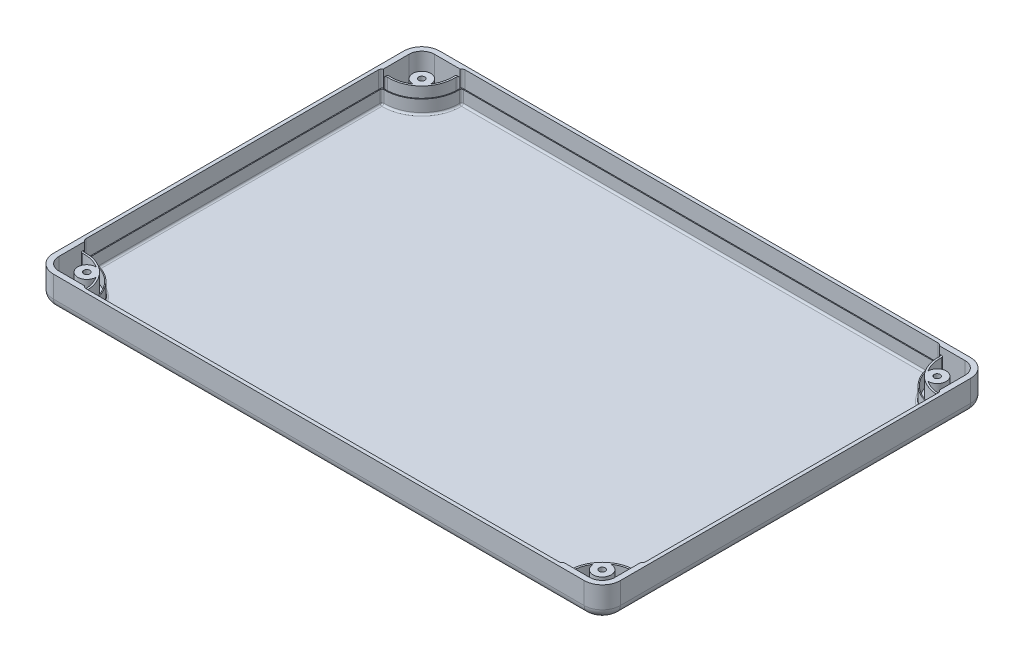
SolidWorks part; units mm, degrees
ref_plane "Alzado" through (0, 0, 0) normal (0, 0, 1) x (1, 0, 0)
ref_plane "Planta" through (0, 0, 0) normal (0, 1, 0) x (1, 0, 0)
ref_plane "Vista lateral" through (0, 0, 0) normal (1, 0, 0) x (0, 0, -1)
sketch "Croquis1" plane through (0, 0, 0) normal (0, 1, 0) x (1, 0, 0)
  line L1 (-147, 107) -> (147, 107)
  line L2 (-157, 97) -> (-157, -97)
  line L3 (-147, -107) -> (147, -107)
  line L4 (157, 97) -> (157, -97)
  line L5 (-157, 107) -> (157, -107) construction
  line L6 (-157, -107) -> (157, 107) construction
  arc A0 (-157, 97) -> (-147, 107) centre (-147, 97) cw
  arc A1 (-147, -107) -> (-157, -97) centre (-147, -97) cw
  arc A2 (157, -97) -> (147, -107) centre (147, -97) cw
  arc A3 (157, 97) -> (147, 107) centre (147, 97) ccw
  point P0 (0, 0)
  dimension "D1" = 10
  dimension "D2" = 10
  dimension "D3" = 10
  dimension "D4" = 10
extrude "Saliente-Extruir1" add sketch "Croquis1" along normal blind 1
sketch "Croquis2" plane through (0, 1, 0) normal (0, 1, 0) x (1, 0, 0)
  line L5 (-147, 107) -> (147, 107)
  line L6 (-157, 97) -> (-157, -97)
  line L7 (-147, -107) -> (147, -107)
  line L8 (-154, 97) -> (-154, -97)
  line L9 (-147, -104) -> (147, -104)
  line L10 (154, -97) -> (154, 97)
  line L11 (147, 104) -> (-147, 104)
  line L12 (-154, 97) -> (-154, -97)
  line L13 (-147, -104) -> (147, -104)
  line L14 (154, -97) -> (154, 97)
  line L15 (147, 104) -> (-147, 104)
  line L16 (157, 97) -> (157, -97)
  line L17 (-157, 107) -> (157, -107) construction
  line L18 (-157, -107) -> (157, 107) construction
  arc A4 (-147, 107) -> (-157, 97) centre (-147, 97) ccw
  arc A5 (157, 97) -> (147, 107) centre (147, 97) ccw
  arc A6 (-147, -107) -> (-157, -97) centre (-147, -97) cw
  arc A7 (157, -97) -> (147, -107) centre (147, -97) cw
  arc A8 (-147, 104) -> (-154, 97) centre (-147, 97) ccw
  arc A9 (-154, -97) -> (-147, -104) centre (-147, -97) ccw
  arc A10 (147, -104) -> (154, -97) centre (147, -97) ccw
  arc A11 (154, 97) -> (147, 104) centre (147, 97) ccw
  arc A12 (-147, 104) -> (-154, 97) centre (-147, 97) ccw
  arc A13 (-154, -97) -> (-147, -104) centre (-147, -97) ccw
  arc A14 (147, -104) -> (154, -97) centre (147, -97) ccw
  arc A15 (154, 97) -> (147, 104) centre (147, 97) ccw
  point P0 (0, 0)
  dimension "D4" = 10
  dimension "D5" = 10
  dimension "D6" = 10
  dimension "D7" = 10
  dimension "D2" = 214
  dimension "D3" = 314
  dimension "D1" = 3
extrude "Saliente-Extruir2" add sketch "Croquis2" along normal blind 16
sketch "Croquis8" plane through (0, 1, 0) normal (0, 1, 0) x (1, 0, 0)
  line L1 (-151.9497, 101.9497) -> (-134.2775, 84.3988) construction
  line L3 (0, 0) -> (0, 145.3607) construction
  line L5 (0, 0) -> (216.3075, 0) construction
  arc A8 (-147, 104) -> (-154, 97) centre (-147, 97) ccw construction
  circle A9 centre (-142.7258, 92.7891) radius 5
  circle A10 centre (-142.7258, 92.7891) radius 1.7
  circle A11 centre (142.7258, 92.7891) radius 5
  circle A12 centre (142.7258, 92.7891) radius 1.7
  circle A13 centre (142.7258, -92.7891) radius 1.7
  circle A14 centre (142.7258, -92.7891) radius 5
  circle A15 centre (-142.7258, -92.7891) radius 5
  circle A16 centre (-142.7258, -92.7891) radius 1.7
extrude "Saliente-Extruir7" add sketch "Croquis8" along normal blind 12
sketch "Croquis10" plane through (0, 1, 0) normal (0, 1, 0) x (1, 0, 0)
  line L0 (-133.9804, 104) -> (-132.9788, 104)
  line L1 (-154, 83.9804) -> (-154, 82.9788)
  line L2 (0, 0) -> (0, 147.7503) construction
  line L3 (0, 0) -> (209.7639, 0) construction
  line L4 (133.9804, 104) -> (132.9788, 104)
  line L5 (154, 83.9804) -> (154, 82.9788)
  line L6 (133.9804, -104) -> (132.9788, -104)
  line L7 (154, -83.9804) -> (154, -82.9788)
  line L8 (-133.9804, -104) -> (-132.9788, -104)
  line L9 (-154, -83.9804) -> (-154, -82.9788)
  arc A0 (-152.9447, 83.9773) -> (-133.9773, 102.9447) centre (-151.9497, 101.9497) ccw
  arc A1 (-147, 104) -> (-154, 97) centre (-147, 97) ccw construction
  arc A2 (-137.7281, 92.6361) -> (-134.9787, 102.9417) centre (-151.9497, 101.9497) ccw
  arc A3 (-142.5383, 87.7926) -> (-137.7281, 92.6361) centre (-142.7258, 92.7891) ccw
  arc A4 (-152.9417, 84.9787) -> (-142.5383, 87.7926) centre (-151.9497, 101.9497) ccw
  arc A5 (-133.9773, 102.9447) -> (-132.9788, 104) centre (-132.9788, 103) cw
  arc A6 (-154, 82.9788) -> (-152.9447, 83.9773) centre (-153, 82.9788) cw
  arc A7 (-152.9417, 84.9787) -> (-154, 83.9804) centre (-153, 83.9804) ccw
  arc A8 (-133.9804, 104) -> (-134.9787, 102.9417) centre (-133.9804, 103) ccw
  arc A9 (133.9773, 102.9447) -> (132.9788, 104) centre (132.9788, 103) ccw
  arc A10 (133.9804, 104) -> (134.9787, 102.9417) centre (133.9804, 103) cw
  arc A11 (154, 82.9788) -> (152.9447, 83.9773) centre (153, 82.9788) ccw
  arc A12 (152.9417, 84.9787) -> (154, 83.9804) centre (153, 83.9804) cw
  arc A13 (142.5383, 87.7926) -> (137.7281, 92.6361) centre (142.7258, 92.7891) cw
  arc A14 (152.9417, 84.9787) -> (142.5383, 87.7926) centre (151.9497, 101.9497) cw
  arc A15 (137.7281, 92.6361) -> (134.9787, 102.9417) centre (151.9497, 101.9497) cw
  arc A16 (152.9447, 83.9773) -> (133.9773, 102.9447) centre (151.9497, 101.9497) cw
  arc A17 (133.9804, -104) -> (134.9787, -102.9417) centre (133.9804, -103) ccw
  arc A18 (133.9773, -102.9447) -> (132.9788, -104) centre (132.9788, -103) cw
  arc A19 (142.5383, -87.7926) -> (137.7281, -92.6361) centre (142.7258, -92.7891) ccw
  arc A20 (137.7281, -92.6361) -> (134.9787, -102.9417) centre (151.9497, -101.9497) ccw
  arc A21 (152.9417, -84.9787) -> (142.5383, -87.7926) centre (151.9497, -101.9497) ccw
  arc A22 (152.9417, -84.9787) -> (154, -83.9804) centre (153, -83.9804) ccw
  arc A23 (154, -82.9788) -> (152.9447, -83.9773) centre (153, -82.9788) cw
  arc A24 (152.9447, -83.9773) -> (133.9773, -102.9447) centre (151.9497, -101.9497) ccw
  arc A25 (-133.9773, -102.9447) -> (-132.9788, -104) centre (-132.9788, -103) ccw
  arc A26 (-133.9804, -104) -> (-134.9787, -102.9417) centre (-133.9804, -103) cw
  arc A27 (-137.7281, -92.6361) -> (-134.9787, -102.9417) centre (-151.9497, -101.9497) cw
  arc A28 (-142.5383, -87.7926) -> (-137.7281, -92.6361) centre (-142.7258, -92.7891) cw
  arc A29 (-152.9417, -84.9787) -> (-142.5383, -87.7926) centre (-151.9497, -101.9497) cw
  arc A30 (-152.9447, -83.9773) -> (-133.9773, -102.9447) centre (-151.9497, -101.9497) cw
  arc A31 (-154, -82.9788) -> (-152.9447, -83.9773) centre (-153, -82.9788) ccw
  arc A32 (-152.9417, -84.9787) -> (-154, -83.9804) centre (-153, -83.9804) cw
  point P11 (-154, 85.0738)
  dimension "D1" = 1
extrude "Saliente-Extruir11" add sketch "Croquis10" along normal blind 12 contours A8 A2 A6 A0 A5 | A4 A7 L3 A6 A0 | A16 A13 A15 A10 A8 A9 | A16 A11 A10 A12 A14 A5 | A4 A24 A18 L5 A17 A20 | A23 A24 A19 A21 A22 A10 | A32 A29 A1 A30 A31 L3 | A30 A28 A27 A26 L5 A25
sketch "Croquis11" plane through (0, 1, 0) normal (0, 1, 0) x (1, 0, 0)
  line L0 (0, 0) -> (0, 121.5799) construction
  line L1 (0, 0) -> (210.3817, 0) construction
  circle A0 centre (142.7258, 92.7891) radius 1.7
  circle A1 centre (-142.7258, 92.7891) radius 1.7
  circle A2 centre (-142.7258, -92.7891) radius 1.7
  circle A3 centre (142.7258, -92.7891) radius 1.7
extrude "Cortar-Extruir1" cut sketch "Croquis11" against normal blind 12
sketch "Croquis13" plane through (0, 1, 0) normal (0, 1, 0) x (1, 0, 0)
  line L0 (0, 0) -> (0, 220.0824) construction
  line L1 (0, 0) -> (282.8461, 0) construction
  line L2 (-130.976, -105) -> (130.976, -105)
  line L7 (-130.976, 104) -> (130.976, 104)
  line L8 (-154, 80.976) -> (-154, -80.976)
  line L9 (-130.976, -104) -> (130.976, -104)
  line L10 (154, 80.976) -> (154, -80.976)
  line L11 (155, 80.976) -> (155, -80.976)
  line L12 (-130.976, 105) -> (130.976, 105)
  line L13 (-155, 80.976) -> (-155, -80.976)
  line L20 (-154, 97) -> (-154, -97)
  line L21 (-147, -104) -> (147, -104)
  line L22 (154, -97) -> (154, 97)
  line L23 (147, 104) -> (-147, 104)
  line L24 (-154, 80.976) -> (-154, -80.976)
  line L25 (-130.976, -104) -> (130.976, -104)
  line L26 (154, -80.976) -> (154, 80.976)
  line L27 (130.976, 104) -> (-130.976, 104)
  arc A0 (-152.95, 81.9748) -> (-131.9748, 102.95) centre (-151.9497, 101.9497) ccw
  arc A1 (-147, 104) -> (-154, 97) centre (-147, 97) ccw construction
  arc A2 (152.95, 81.9748) -> (131.9748, 102.95) centre (151.9497, 101.9497) cw
  arc A3 (152.95, -81.9748) -> (131.9748, -102.95) centre (151.9497, -101.9497) ccw
  arc A4 (-152.95, -81.9748) -> (-131.9748, -102.95) centre (-151.9497, -101.9497) cw
  arc A5 (-130.976, 104) -> (-131.9748, 102.95) centre (-130.976, 103) ccw
  arc A6 (-154, 80.976) -> (-152.95, 81.9748) centre (-153, 80.976) cw
  arc A7 (131.9748, 102.95) -> (130.976, 104) centre (130.976, 103) ccw
  arc A8 (152.95, 81.9748) -> (154, 80.976) centre (153, 80.976) cw
  arc A9 (154, -80.976) -> (152.95, -81.9748) centre (153, -80.976) cw
  arc A10 (130.976, -104) -> (131.9748, -102.95) centre (130.976, -103) ccw
  arc A11 (-130.976, -104) -> (-131.9748, -102.95) centre (-130.976, -103) cw
  arc A12 (-154, -80.976) -> (-152.95, -81.9748) centre (-153, -80.976) ccw
  arc A13 (-152.9, -82.9735) -> (-132.9735, -102.9) centre (-151.9497, -101.9497) cw
  arc A14 (-130.976, -105) -> (-132.9735, -102.9) centre (-130.976, -103) cw
  arc A15 (130.976, -105) -> (132.9735, -102.9) centre (130.976, -103) ccw
  arc A16 (152.9, -82.9735) -> (132.9735, -102.9) centre (151.9497, -101.9497) ccw
  arc A17 (155, -80.976) -> (152.9, -82.9735) centre (153, -80.976) cw
  arc A18 (152.9, 82.9735) -> (155, 80.976) centre (153, 80.976) cw
  arc A19 (152.9, 82.9735) -> (132.9735, 102.9) centre (151.9497, 101.9497) cw
  arc A20 (132.9735, 102.9) -> (130.976, 105) centre (130.976, 103) ccw
  arc A21 (-147, 104) -> (-154, 97) centre (-147, 97) ccw
  arc A22 (-154, -97) -> (-147, -104) centre (-147, -97) ccw
  arc A23 (147, -104) -> (154, -97) centre (147, -97) ccw
  arc A24 (154, 97) -> (147, 104) centre (147, 97) ccw
  arc A25 (-130.976, 105) -> (-132.9735, 102.9) centre (-130.976, 103) ccw
  arc A26 (-152.9, 82.9735) -> (-132.9735, 102.9) centre (-151.9497, 101.9497) ccw
  arc A27 (-155, 80.976) -> (-152.9, 82.9735) centre (-153, 80.976) cw
  arc A28 (-155, -80.976) -> (-152.9, -82.9735) centre (-153, -80.976) ccw
  dimension "D1" = 1
  dimension "D2" = 3
  dimension "D3" = 1
extrude "Cortar-Extruir2" cut sketch "Croquis13" along normal blind 16 contours L12 A20 A19 A18 L11 A17 A16 A15 L2 A14 A13 A28 L13 A27 A26 A25
sketch "Croquis14" plane through (0, 1, 0) normal (0, 1, 0) x (1, 0, 0)
  line L0 (0, 0) -> (0, 172.0527) construction
  line L1 (0, 0) -> (242.4053, 0) construction
  line L2 (153.2596, 103.5) -> (153.5, 103.5)
  line L3 (-153.5, 103.5) -> (-153.2596, 103.5)
  line L4 (-153.5, 80.4568) -> (-153.5, -80.4568)
  line L5 (-153.5, -103.5) -> (-153.2596, -103.5)
  line L6 (153.5, 80.4568) -> (153.5, -80.4568)
  line L7 (-135.1367, 91.1182) -> (135.1367, -91.1182) construction
  line L8 (-135.1367, -91.1182) -> (135.1367, 91.1182) construction
  line L9 (-130.976, 104) -> (130.976, 104)
  line L10 (-154, 80.976) -> (-154, -80.976)
  line L11 (-130.976, -104) -> (130.976, -104)
  line L12 (154, 80.976) -> (154, -80.976)
  line L13 (-154, 104) -> (-153.2596, 103.5) construction
  line L14 (-154, -104) -> (-153.2596, -103.5) construction
  line L15 (153.2596, 103.5) -> (154, 104) construction
  line L16 (153.2596, -103.5) -> (154, -104) construction
  line L17 (153.2596, -103.5) -> (153.5, -103.5)
  line L18 (-135.0728, -91.218) -> (135.0728, 91.218) construction
  line L19 (-130.4568, -103.5) -> (130.4568, -103.5)
  line L20 (-135.0728, 91.218) -> (135.0728, -91.218) construction
  line L21 (-130.4568, 103.5) -> (130.4568, 103.5)
  arc A0 (-152.95, 81.9748) -> (-131.9748, 102.95) centre (-151.9497, 101.9497) ccw
  arc A1 (-147, 104) -> (-154, 97) centre (-147, 97) ccw construction
  arc A2 (-152.4744, 81.4565) -> (-131.4565, 102.4744) centre (-151.9497, 101.9497) ccw
  arc A3 (152.4744, 81.4565) -> (131.4565, 102.4744) centre (151.9497, 101.9497) cw
  arc A4 (152.95, 81.9748) -> (131.9748, 102.95) centre (151.9497, 101.9497) cw
  arc A5 (152.4744, -81.4565) -> (131.4565, -102.4744) centre (151.9497, -101.9497) ccw
  arc A6 (152.95, -81.9748) -> (131.9748, -102.95) centre (151.9497, -101.9497) ccw
  arc A7 (-152.4744, -81.4565) -> (-131.4565, -102.4744) centre (-151.9497, -101.9497) cw
  arc A8 (-152.95, -81.9748) -> (-131.9748, -102.95) centre (-151.9497, -101.9497) cw
  arc A9 (-131.9748, 102.95) -> (-130.976, 104) centre (-130.976, 103) cw
  arc A10 (-130.4568, 103.5) -> (-131.4565, 102.4744) centre (-130.4568, 102.5) ccw
  arc A11 (-152.95, 81.9748) -> (-154, 80.976) centre (-153, 80.976) ccw
  arc A12 (-153.5, 80.4568) -> (-152.4744, 81.4565) centre (-152.5, 80.4568) cw
  arc A13 (-152.4744, -81.4565) -> (-153.5, -80.4568) centre (-152.5, -80.4568) cw
  arc A14 (-152.95, -81.9748) -> (-154, -80.976) centre (-153, -80.976) cw
  arc A15 (-131.9748, -102.95) -> (-130.976, -104) centre (-130.976, -103) ccw
  arc A16 (-130.4568, -103.5) -> (-131.4565, -102.4744) centre (-130.4568, -102.5) cw
  arc A17 (131.9748, -102.95) -> (130.976, -104) centre (130.976, -103) cw
  arc A18 (130.4568, -103.5) -> (131.4565, -102.4744) centre (130.4568, -102.5) ccw
  arc A19 (153.5, -80.4568) -> (152.4744, -81.4565) centre (152.5, -80.4568) cw
  arc A20 (154, -80.976) -> (152.95, -81.9748) centre (153, -80.976) cw
  arc A21 (131.9748, 102.95) -> (130.976, 104) centre (130.976, 103) ccw
  arc A22 (131.4565, 102.4744) -> (130.4568, 103.5) centre (130.4568, 102.5) ccw
  arc A23 (154, 80.976) -> (152.95, 81.9748) centre (153, 80.976) ccw
  arc A24 (152.4744, 81.4565) -> (153.5, 80.4568) centre (152.5, 80.4568) cw
  dimension "D1" = 207
  dimension "D5" = 1
  dimension "D6" = 1
  dimension "D2" = 307
  dimension "D3" = 208
  dimension "D4" = 308
extrude "Saliente-Extruir12" add sketch "Croquis14" along normal blind 7.5 contours L12 A23 A4 A21 L9 A9 A0 A11 L10 A14 A8 A15 L11 A17 A6 A20 A3 A24 L6 A19 A5 A18 L19 A16 A7 A13 L4 A12 A2 A10 L21 A22
fillet "Redondeo1" radius 5 8 edges at (154.0711, 0, 104.0711) (0, 0, 107) (-154.0711, 0, 104.0711) (-157, 0, 0) (-154.0711, 0, -104.0711) (0, 0, -107) (154.0711, 0, -104.0711) (157, 0, 0)
fillet "Redondeo2" radius 1 16 edges at (153.198, 1, -81.1729) (137.4541, 1, -87.4541) (131.1729, 1, -103.198) (0, 1, -103.5) (-131.1729, 1, -103.198) (-137.4541, 1, -87.4541) (-153.198, 1, -81.1729) (-153.5, 1, 0) (-153.198, 1, 81.1729) (-137.4541, 1, 87.4541) (-131.1729, 1, 103.198) (0, 1, 103.5) (131.1729, 1, 103.198) (137.4541, 1, 87.4541) (153.198, 1, 81.1729) (153.5, 1, 0)
